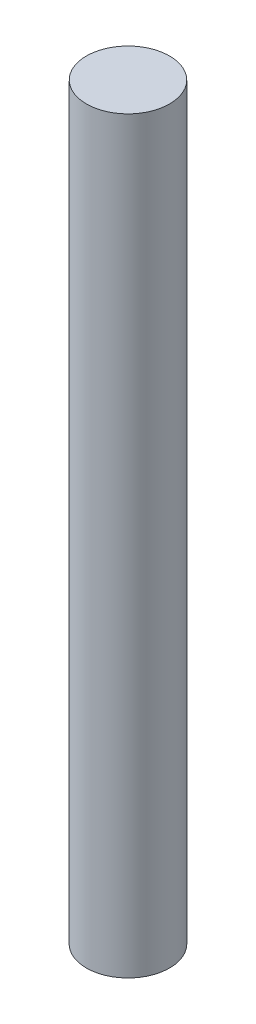
SolidWorks part; units mm, degrees
ref_plane "Ön Düzlem" through (0, 0, 0) normal (0, 0, 1) x (1, 0, 0)
ref_plane "Üst Düzlem" through (0, 0, 0) normal (0, 1, 0) x (1, 0, 0)
ref_plane "Sağ Düzlem" through (0, 0, 0) normal (1, 0, 0) x (0, 0, -1)
sketch "Çizim1" plane through (0, 0, 0) normal (0, 1, 0) x (1, 0, 0)
  circle A0 centre (0, 0) radius 25
extrude "Yükseklik-Ekstrüzyon1" add sketch "Çizim1" along normal blind 450
